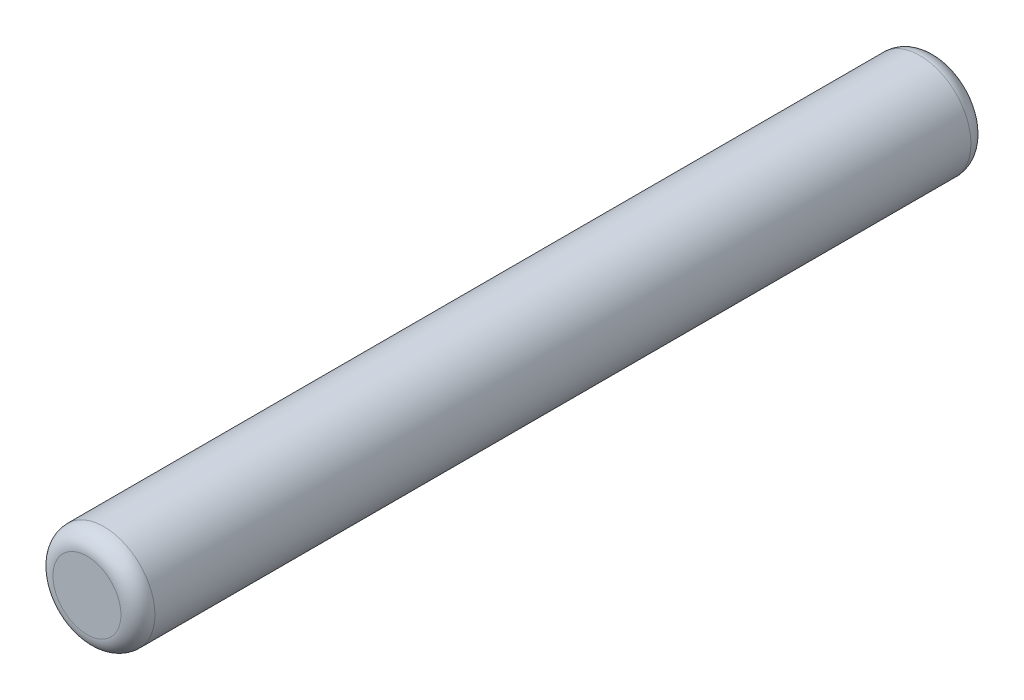
SolidWorks part; units mm, degrees
material "S45C"
ref_plane "正面" through (0, 0, 0) normal (0, 0, 1) x (1, 0, 0)
ref_plane "平面" through (0, 0, 0) normal (0, 1, 0) x (1, 0, 0)
ref_plane "右側面" through (0, 0, 0) normal (1, 0, 0) x (0, 0, -1)
sketch "ｽｹｯﾁ1" plane through (0, 0, 0) normal (0, 0, 1) x (1, 0, 0)
  circle A0 centre (0, 0) radius 1.5
  dimension "D1" = 3
extrude "ﾎﾞｽ - 押し出し1" add sketch "ｽｹｯﾁ1" along normal mid plane 25
fillet "ﾌｨﾚｯﾄ1" radius 0.5 2 edges at (1.5, 0, -12.5) (1.5, 0, 12.5)
